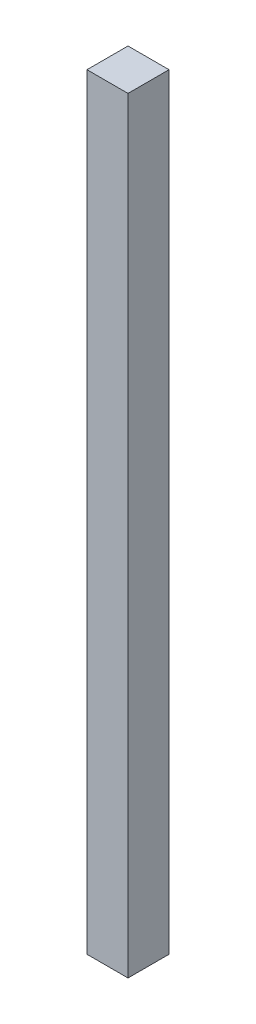
SolidWorks part; units mm, degrees
ref_plane "Front Plane" through (0, 0, 0) normal (0, 0, 1) x (1, 0, 0)
ref_plane "Top Plane" through (0, 0, 0) normal (0, 1, 0) x (1, 0, 0)
ref_plane "Right Plane" through (0, 0, 0) normal (1, 0, 0) x (0, 0, -1)
sketch "Sketch1" plane through (0, 0, 0) normal (0, 1, 0) x (1, 0, 0)
  line L1 (19.05, -19.05) -> (-19.05, -19.05)
  line L2 (19.05, -19.05) -> (19.05, 19.05)
  line L3 (19.05, 19.05) -> (-19.05, 19.05)
  line L4 (-19.05, -19.05) -> (-19.05, 19.05)
  line L5 (19.05, -19.05) -> (-19.05, 19.05) construction
  line L6 (19.05, 19.05) -> (-19.05, -19.05) construction
  point P0 (0, 0)
  dimension "D1" = 38.1
  dimension "D2" = 38.1
extrude "Boss-Extrude1" add sketch "Sketch1" along normal blind 711.2
